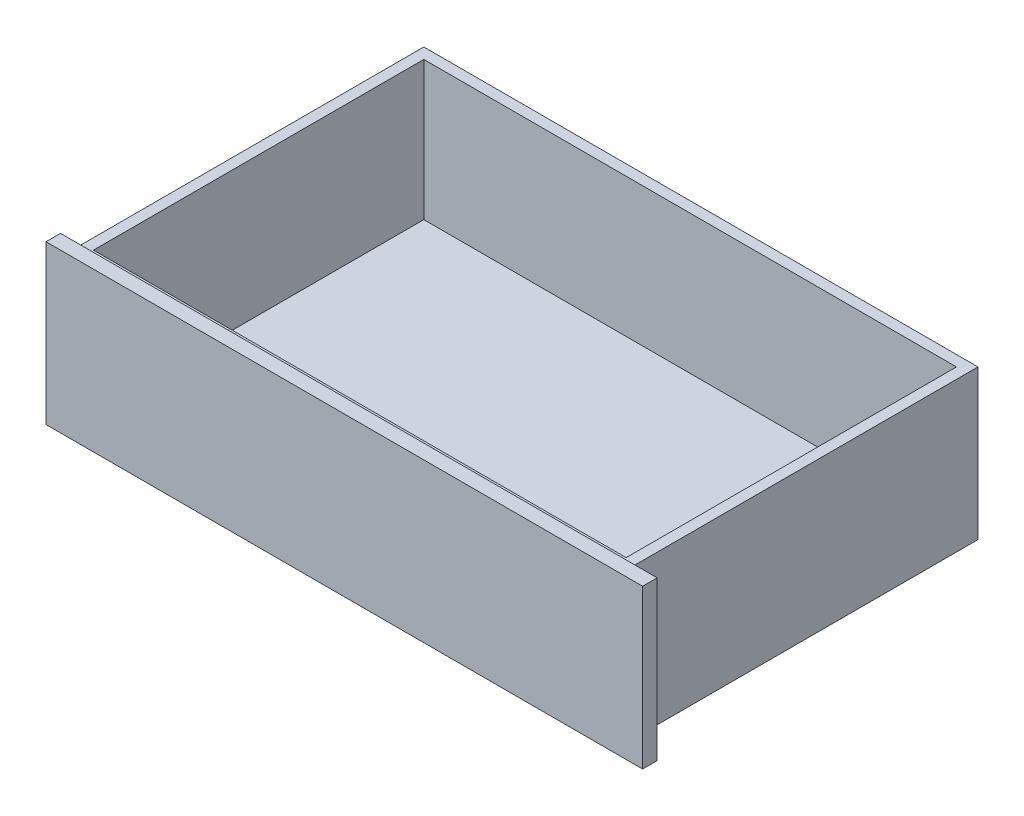
SolidWorks part; units mm, degrees
material "Maple"
ref_plane "Front Plane" through (0, 0, 0) normal (0, 0, 1) x (1, 0, 0)
ref_plane "Top Plane" through (0, 0, 0) normal (0, 1, 0) x (1, 0, 0)
ref_plane "Right Plane" through (0, 0, 0) normal (1, 0, 0) x (0, 0, -1)
sketch "Sketch1" plane through (0, 0, 0) normal (0, 1, 0) x (1, 0, 0)
  line L1 (-315, -200) -> (315, -200)
  line L2 (-315, -200) -> (-315, 200)
  line L3 (-315, 200) -> (315, 200)
  line L4 (315, -200) -> (315, 200)
  line L5 (-315, -200) -> (315, 200) construction
  line L6 (-315, 200) -> (315, -200) construction
  point P0 (0, 0)
  dimension "D1" = 630
  dimension "D2" = 400
extrude "Extrusion" add sketch "Sketch1" along normal blind 170
shell "Drawer's interior" thickness 12.2428
sketch "Sketch2" plane through (0, 0, 200) normal (0, 0, 1) x (1, 0, 0)
  line L0 (-315, 0) -> (315, 0) construction
  line L1 (-351.5, -5) -> (351.5, -5)
  line L2 (-351.5, -5) -> (-351.5, 175)
  line L3 (-351.5, 175) -> (351.5, 175)
  line L4 (351.5, -5) -> (351.5, 175)
  line L5 (-351.5, -5) -> (351.5, 175) construction
  line L6 (-351.5, 175) -> (351.5, -5) construction
  line L7 (315, 170) -> (315, 0) construction
  point P0 (0, 85)
  point P8 (0, 0)
  point P14 (315, 85)
  dimension "D1" = 703
  dimension "D2" = 180
extrude "Boss-Extrude2" [suppressed] add sketch "Sketch2" along normal blind 17 contours L4 L3 L2 L1
sketch "Sketch3" plane through (0, 0, 200) normal (0, 0, 1) x (1, 0, 0)
  line L0 (315, 170) -> (315, 0) construction
  line L1 (-328, 180) -> (350.2428, 180)
  line L2 (-328, 180) -> (-328, 0)
  line L4 (350.2428, 180) -> (350.2428, 0)
  line L5 (-315, 170) -> (-315, 0) construction
  line L6 (-315, 170) -> (315, 170) construction
  line L8 (-328, 0) -> (350.2428, 0)
  line L9 (-315, 0) -> (315, 0) construction
  dimension "D1" = 35.2428
  dimension "D2" = 13
  dimension "D3" = 10
  dimension "D4" = 0
extrude "Boss-Extrude3" add sketch "Sketch3" along normal blind 16.5
equation "\"D1@Drawer's interior\"=\"Drawer_side_tickness@Drawer Assembly Narrow.Assembly\""
equation "\"D2@Sketch1\"=\"Drawer_length@Drawer Assembly Narrow.Assembly\""
equation "\"D3@Sketch3\"=\"Drawer_top_clearance@Drawer Assembly Narrow.Assembly\""
equation "\"D1@Sketch3\"=\"Drawer­_to_sidewall@Drawer Assembly Narrow.Assembly\"+\"Drawer_side_tickness@Drawer Assembly Narrow.Assembly\""
